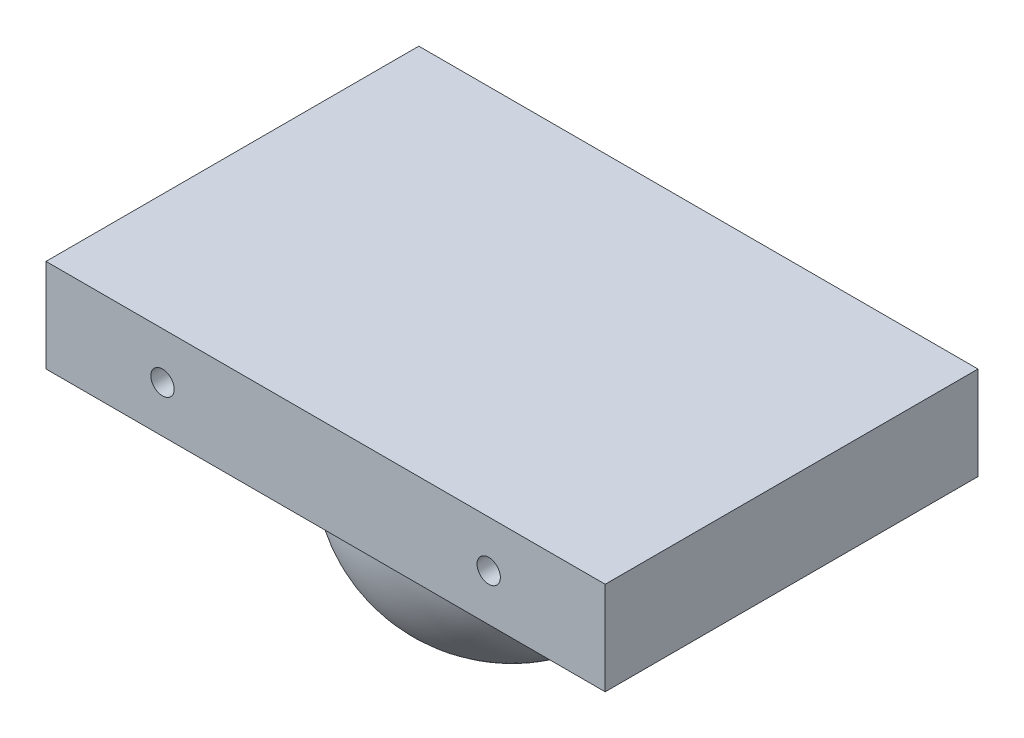
SolidWorks part; units mm, degrees
ref_plane "Front Plane" through (0, 0, 0) normal (0, 0, 1) x (1, 0, 0)
ref_plane "Top Plane" through (0, 0, 0) normal (0, 1, 0) x (1, 0, 0)
ref_plane "Right Plane" through (0, 0, 0) normal (1, 0, 0) x (0, 0, -1)
sketch "Sketch2" plane through (0, 0, 0) normal (0, 1, 0) x (1, 0, 0)
  line L1 (-18.9349, 10.2367) -> (11.0651, 10.2367)
  line L2 (-18.9349, 10.2367) -> (-18.9349, -9.7633)
  line L3 (-18.9349, -9.7633) -> (11.0651, -9.7633)
  line L4 (11.0651, 10.2367) -> (11.0651, -9.7633)
  dimension "D1" = 20
  dimension "D2" = 30
extrude "Boss-Extrude2" add sketch "Sketch2" along normal blind 5
sketch "Sketch3" plane through (0, 0, 0) normal (0, -1, 0) x (1, 0, 0)
  circle A0 centre (-3.9349, -0.2367) radius 5
extrude "Boss-Extrude3" add sketch "Sketch3" along normal blind 2 contours A0
sketch "Sketch4" plane through (0, -2, 0) normal (0, -1, 0) x (-1, 0, 0)
  line L0 (3.9349, -7.2633) -> (3.9349, 7.7367)
  arc A2 (3.9349, -7.2633) -> (3.9349, 7.7367) centre (3.9349, 0.2367) ccw
revolve "Revolve1" add sketch "Sketch4" angle 180 about L0
sketch "Sketch5" plane through (0, 0, 9.7633) normal (0, 0, 1) x (1, 0, 0)
  circle A0 centre (-12.6849, 2.5) radius 0.625
  circle A1 centre (4.8151, 2.5) radius 0.625
  dimension "D3" = 1.25
  dimension "D4" = 1.25
extrude "Cut-Extrude2" cut sketch "Sketch5" against normal blind 20
